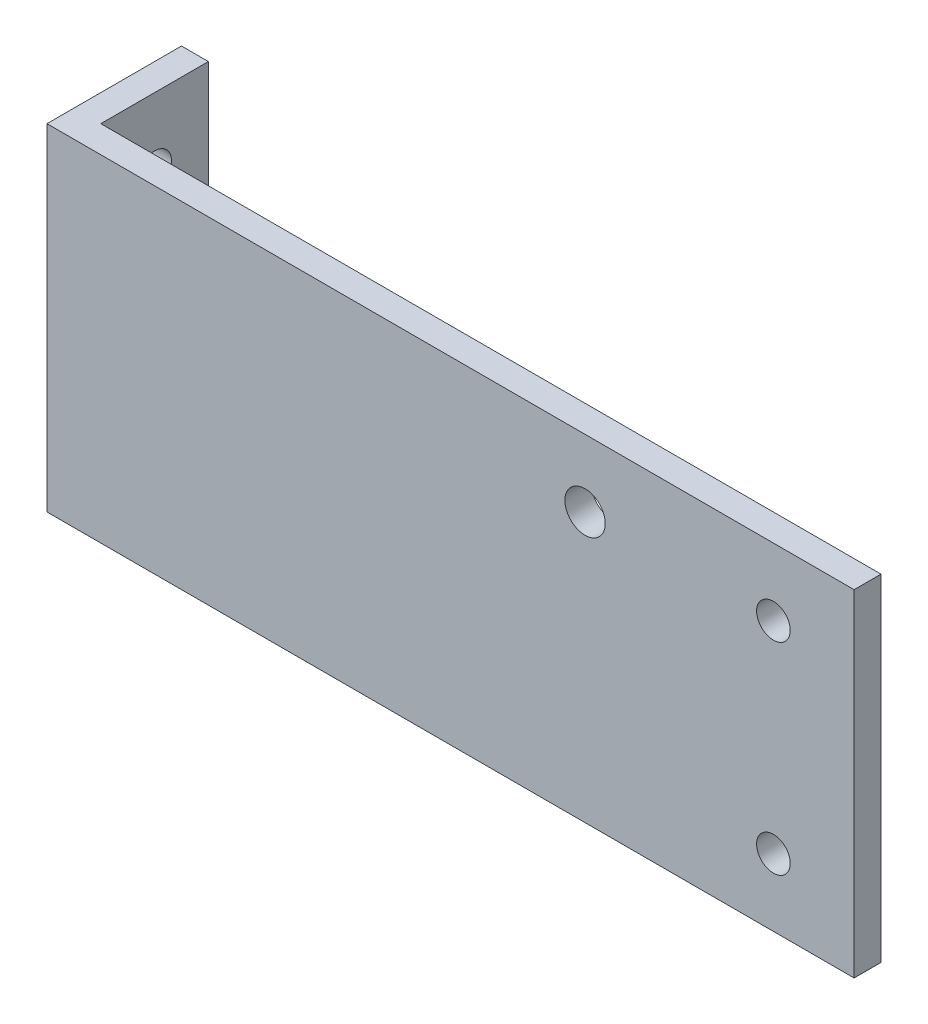
SolidWorks part; units mm, degrees
ref_plane "Спереди" through (0, 0, 0) normal (0, 0, 1) x (1, 0, 0)
ref_plane "Сверху" through (0, 0, 0) normal (0, 1, 0) x (1, 0, 0)
ref_plane "Справа" through (0, 0, 0) normal (1, 0, 0) x (0, 0, -1)
sketch "Эскиз1" plane through (0, 0, 0) normal (0, 1, 0) x (1, 0, 0)
  line L1 (0, 0) -> (120, 0)
  line L2 (0, 0) -> (0, 4)
  line L3 (4, 4) -> (120, 4)
  line L4 (120, 0) -> (120, 4)
  line L6 (0, 4) -> (0, 20)
  line L7 (0, 20) -> (4, 20)
  line L8 (4, 4) -> (4, 20)
  dimension "D1" = 120
  dimension "D2" = 4
  dimension "D3" = 20
  dimension "D4" = 4
extrude "Бобышка-Вытянуть1" add sketch "Эскиз1" along normal blind 50
sketch "Эскиз2" plane through (0, 0, 0) normal (-1, 0, 0) x (0, 0, 1)
  line L0 (-12, 44.9311) -> (-12, 11.555) construction
  line L2 (-20, 0) -> (0, 0) construction
  line L3 (0, 50) -> (0, 0) construction
  circle A0 centre (-12, 40) radius 2.5
  circle A1 centre (-12, 10) radius 2.5
  dimension "D2" = 5
  dimension "D3" = 5
  dimension "D1" = 12
  dimension "D4" = 30
  dimension "D5" = 10
extrude "Вырез-Вытянуть1" cut sketch "Эскиз2" against normal blind 10
sketch "Эскиз3" plane through (0, 0, 0) normal (0, 0, 1) x (1, 0, 0)
  line L0 (108, 46.6766) -> (108, 6.7064) construction
  line L1 (120, 50) -> (120, 0) construction
  line L2 (0, 0) -> (120, 0) construction
  line L3 (120, 50) -> (4, 50) construction
  line L4 (0, 50) -> (0, 0) construction
  circle A0 centre (108, 40) radius 2.5
  circle A1 centre (108, 10) radius 2.5
  circle A2 centre (80, 40) radius 3
  dimension "D2" = 5
  dimension "D3" = 5
  dimension "D6" = 6
  dimension "D1" = 12
  dimension "D4" = 30
  dimension "D5" = 10
  dimension "D7" = 10
  dimension "D8" = 80
extrude "Вырез-Вытянуть2" cut sketch "Эскиз3" against normal blind 10
